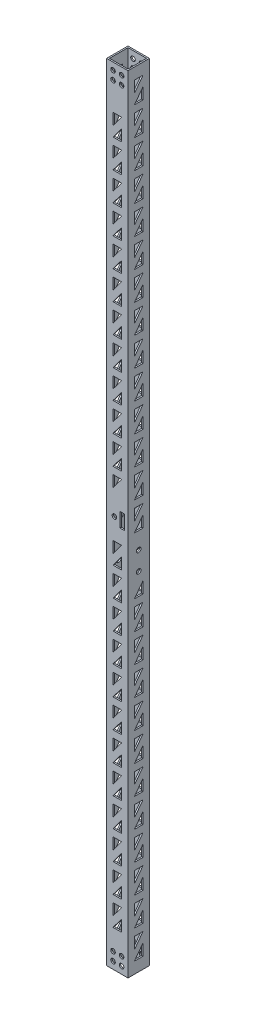
SolidWorks part; units mm, degrees
ref_plane "前视基准面" through (0, 0, 0) normal (0, 0, 1) x (1, 0, 0)
ref_plane "上视基准面" through (0, 0, 0) normal (0, 1, 0) x (1, 0, 0)
ref_plane "右视基准面" through (0, 0, 0) normal (1, 0, 0) x (0, 0, -1)
other "Configuration Table"
sketch "草图1" plane through (0, 0, 0) normal (0, 1, 0) x (1, 0, 0)
  line L1 (6.5, -6.5) -> (-6.5, -6.5)
  line L2 (6.5, -6.5) -> (6.5, 6.5)
  line L3 (6.5, 6.5) -> (-6.5, 6.5)
  line L4 (-6.5, -6.5) -> (-6.5, 6.5)
  line L5 (6.5, -6.5) -> (-6.5, 6.5) construction
  line L6 (6.5, 6.5) -> (-6.5, -6.5) construction
  line L7 (7.5, -7.5) -> (-7.5, -7.5)
  line L8 (7.5, -7.5) -> (7.5, 7.5)
  line L9 (7.5, 7.5) -> (-7.5, 7.5)
  line L10 (-7.5, -7.5) -> (-7.5, 7.5)
  line L11 (7.5, -7.5) -> (-7.5, 7.5) construction
  line L12 (7.5, 7.5) -> (-7.5, -7.5) construction
  point P0 (0, 0)
  point P6 (0, 0)
  dimension "D1" = 13
  dimension "D2" = 15
extrude "凸台-拉伸1" add sketch "草图1" along normal blind 551
sketch "草图2" plane through (0, 0, 7.5) normal (0, 0, 1) x (1, 0, 0)
  line L0 (-7.5, 543) -> (7.5, 543) construction
  line L1 (-7.5, 551) -> (-7.5, 0) construction
  line L2 (7.5, 551) -> (7.5, 0) construction
  line L3 (-7.5, 275.5) -> (7.5, 275.5) construction
  line L4 (-7.5, 551) -> (7.5, 551) construction
  line L5 (0, 549.2213) -> (0, 545.4151) construction
  line L6 (-7.5, 525.5) -> (7.5, 525.5) construction
  line L7 (-7.5, 25.5) -> (7.5, 25.5) construction
  line L8 (-3, 512.5) -> (-3, 520.5)
  line L9 (-3, 520.5) -> (3, 520.5)
  line L10 (3, 520.5) -> (-3, 512.5)
  line L11 (-3, 505.5) -> (3, 505.5)
  line L12 (3, 505.5) -> (3, 513.5)
  line L13 (3, 513.5) -> (-3, 505.5)
  line L14 (3, 500.5) -> (-3, 492.5)
  line L15 (-3, 492.5) -> (-3, 500.5)
  line L16 (-3, 500.5) -> (3, 500.5)
  line L17 (3, 493.5) -> (-3, 485.5)
  line L18 (-3, 485.5) -> (3, 485.5)
  line L19 (3, 485.5) -> (3, 493.5)
  line L20 (3, 480.5) -> (-3, 472.5)
  line L21 (-3, 472.5) -> (-3, 480.5)
  line L22 (-3, 480.5) -> (3, 480.5)
  line L23 (3, 473.5) -> (-3, 465.5)
  line L24 (-3, 465.5) -> (3, 465.5)
  line L25 (3, 465.5) -> (3, 473.5)
  line L26 (3, 460.5) -> (-3, 452.5)
  line L27 (-3, 452.5) -> (-3, 460.5)
  line L28 (-3, 460.5) -> (3, 460.5)
  line L29 (3, 453.5) -> (-3, 445.5)
  line L30 (-3, 445.5) -> (3, 445.5)
  line L31 (3, 445.5) -> (3, 453.5)
  line L32 (3, 440.5) -> (-3, 432.5)
  line L33 (-3, 432.5) -> (-3, 440.5)
  line L34 (-3, 440.5) -> (3, 440.5)
  line L35 (3, 433.5) -> (-3, 425.5)
  line L36 (-3, 425.5) -> (3, 425.5)
  line L37 (3, 425.5) -> (3, 433.5)
  line L38 (3, 420.5) -> (-3, 412.5)
  line L39 (-3, 412.5) -> (-3, 420.5)
  line L40 (-3, 420.5) -> (3, 420.5)
  line L41 (3, 413.5) -> (-3, 405.5)
  line L42 (-3, 405.5) -> (3, 405.5)
  line L43 (3, 405.5) -> (3, 413.5)
  line L44 (3, 400.5) -> (-3, 392.5)
  line L45 (-3, 392.5) -> (-3, 400.5)
  line L46 (-3, 400.5) -> (3, 400.5)
  line L47 (3, 393.5) -> (-3, 385.5)
  line L48 (-3, 385.5) -> (3, 385.5)
  line L49 (3, 385.5) -> (3, 393.5)
  line L50 (3, 380.5) -> (-3, 372.5)
  line L51 (-3, 372.5) -> (-3, 380.5)
  line L52 (-3, 380.5) -> (3, 380.5)
  line L53 (3, 373.5) -> (-3, 365.5)
  line L54 (-3, 365.5) -> (3, 365.5)
  line L55 (3, 365.5) -> (3, 373.5)
  line L56 (3, 360.5) -> (-3, 352.5)
  line L57 (-3, 352.5) -> (-3, 360.5)
  line L58 (-3, 360.5) -> (3, 360.5)
  line L59 (3, 353.5) -> (-3, 345.5)
  line L60 (-3, 345.5) -> (3, 345.5)
  line L61 (3, 345.5) -> (3, 353.5)
  line L62 (3, 340.5) -> (-3, 332.5)
  line L63 (-3, 332.5) -> (-3, 340.5)
  line L64 (-3, 340.5) -> (3, 340.5)
  line L65 (3, 333.5) -> (-3, 325.5)
  line L66 (-3, 325.5) -> (3, 325.5)
  line L67 (3, 325.5) -> (3, 333.5)
  line L68 (3, 320.5) -> (-3, 312.5)
  line L69 (-3, 312.5) -> (-3, 320.5)
  line L70 (-3, 320.5) -> (3, 320.5)
  line L71 (3, 313.5) -> (-3, 305.5)
  line L72 (-3, 305.5) -> (3, 305.5)
  line L73 (3, 305.5) -> (3, 313.5)
  line L74 (3, 300.5) -> (-3, 292.5)
  line L75 (-3, 292.5) -> (-3, 300.5)
  line L76 (-3, 300.5) -> (3, 300.5)
  line L95 (3, 233.5) -> (-3, 225.5)
  line L96 (-3, 225.5) -> (3, 225.5)
  line L97 (3, 225.5) -> (3, 233.5)
  line L98 (3, 220.5) -> (-3, 212.5)
  line L99 (-3, 212.5) -> (-3, 220.5)
  line L100 (-3, 220.5) -> (3, 220.5)
  line L101 (3, 213.5) -> (-3, 205.5)
  line L102 (-3, 205.5) -> (3, 205.5)
  line L103 (3, 205.5) -> (3, 213.5)
  line L104 (3, 200.5) -> (-3, 192.5)
  line L105 (-3, 192.5) -> (-3, 200.5)
  line L106 (-3, 200.5) -> (3, 200.5)
  line L107 (3, 193.5) -> (-3, 185.5)
  line L108 (-3, 185.5) -> (3, 185.5)
  line L109 (3, 185.5) -> (3, 193.5)
  line L110 (3, 180.5) -> (-3, 172.5)
  line L111 (-3, 172.5) -> (-3, 180.5)
  line L112 (-3, 180.5) -> (3, 180.5)
  line L113 (3, 173.5) -> (-3, 165.5)
  line L114 (-3, 165.5) -> (3, 165.5)
  line L115 (3, 165.5) -> (3, 173.5)
  line L116 (3, 160.5) -> (-3, 152.5)
  line L117 (-3, 152.5) -> (-3, 160.5)
  line L118 (-3, 160.5) -> (3, 160.5)
  line L119 (3, 153.5) -> (-3, 145.5)
  line L120 (-3, 145.5) -> (3, 145.5)
  line L121 (3, 145.5) -> (3, 153.5)
  line L122 (3, 140.5) -> (-3, 132.5)
  line L123 (-3, 132.5) -> (-3, 140.5)
  line L124 (-3, 140.5) -> (3, 140.5)
  line L125 (3, 133.5) -> (-3, 125.5)
  line L126 (-3, 125.5) -> (3, 125.5)
  line L127 (3, 125.5) -> (3, 133.5)
  line L128 (3, 120.5) -> (-3, 112.5)
  line L129 (-3, 112.5) -> (-3, 120.5)
  line L130 (-3, 120.5) -> (3, 120.5)
  line L131 (3, 113.5) -> (-3, 105.5)
  line L132 (-3, 105.5) -> (3, 105.5)
  line L133 (3, 105.5) -> (3, 113.5)
  line L134 (3, 100.5) -> (-3, 92.5)
  line L135 (-3, 92.5) -> (-3, 100.5)
  line L136 (-3, 100.5) -> (3, 100.5)
  line L137 (3, 93.5) -> (-3, 85.5)
  line L138 (-3, 85.5) -> (3, 85.5)
  line L139 (3, 85.5) -> (3, 93.5)
  line L140 (3, 80.5) -> (-3, 72.5)
  line L141 (-3, 72.5) -> (-3, 80.5)
  line L142 (-3, 80.5) -> (3, 80.5)
  line L143 (3, 73.5) -> (-3, 65.5)
  line L144 (-3, 65.5) -> (3, 65.5)
  line L145 (3, 65.5) -> (3, 73.5)
  line L146 (3, 60.5) -> (-3, 52.5)
  line L147 (-3, 52.5) -> (-3, 60.5)
  line L148 (-3, 60.5) -> (3, 60.5)
  line L149 (3, 53.5) -> (-3, 45.5)
  line L150 (-3, 45.5) -> (3, 45.5)
  line L151 (3, 45.5) -> (3, 53.5)
  line L152 (3, 40.5) -> (-3, 32.5)
  line L153 (-3, 32.5) -> (-3, 40.5)
  line L154 (-3, 40.5) -> (3, 40.5)
  line L155 (3, 33.5) -> (-3, 25.5)
  line L156 (-3, 25.5) -> (3, 25.5)
  line L157 (3, 25.5) -> (3, 33.5)
  line L158 (3, 253.5) -> (-3, 245.5) [skipped]
  line L159 (3, 245.5) -> (3, 253.5) [skipped]
  line L160 (-3, 245.5) -> (3, 245.5) [skipped]
  line L161 (-3, 252.5) -> (-3, 260.5) [skipped]
  line L162 (-3, 260.5) -> (3, 260.5) [skipped]
  line L163 (3, 260.5) -> (-3, 252.5) [skipped]
  line L164 (-3, 232.5) -> (-3, 240.5) [skipped]
  line L165 (-3, 240.5) -> (3, 240.5) [skipped]
  line L166 (3, 240.5) -> (-3, 232.5) [skipped]
  line L167 (3, 260.5) -> (-3, 252.5)
  line L168 (-3, 252.5) -> (-3, 260.5)
  line L169 (-3, 260.5) -> (3, 260.5)
  line L170 (3, 240.5) -> (-3, 232.5)
  line L171 (-3, 232.5) -> (-3, 240.5)
  line L172 (-3, 240.5) -> (3, 240.5)
  line L173 (3, 253.5) -> (-3, 245.5)
  line L174 (-3, 245.5) -> (3, 245.5)
  line L175 (3, 245.5) -> (3, 253.5)
  line L176 (3, 280.5) -> (-3, 272.5) [skipped]
  line L177 (-3, 272.5) -> (-3, 280.5) [skipped]
  line L178 (-3, 280.5) -> (3, 280.5) [skipped]
  line L179 (3, 293.5) -> (-3, 285.5) [skipped]
  line L180 (-3, 285.5) -> (3, 285.5) [skipped]
  line L181 (3, 285.5) -> (3, 293.5) [skipped]
  line L182 (3, 273.5) -> (-3, 265.5) [skipped]
  line L183 (-3, 265.5) -> (3, 265.5) [skipped]
  line L184 (3, 265.5) -> (3, 273.5) [skipped]
  line L186 (1.95, 270.45) -> (5.05, 270.45)
  line L187 (1.95, 270.45) -> (1.95, 280.55)
  line L188 (1.95, 280.55) -> (5.05, 280.55)
  line L189 (5.05, 270.45) -> (5.05, 280.55)
  line L190 (1.95, 270.45) -> (5.05, 280.55) construction
  line L191 (1.95, 280.55) -> (5.05, 270.45) construction
  circle A0 centre (-3, 546) radius 1.6
  circle A1 centre (3, 546) radius 1.6
  circle A2 centre (-3, 540) radius 1.6
  circle A3 centre (3, 540) radius 1.6
  circle A4 centre (3, 11) radius 1.6
  circle A5 centre (-3, 11) radius 1.6
  circle A6 centre (3, 5) radius 1.6
  circle A7 centre (-3, 5) radius 1.6
  circle A8 centre (-2, 275.5) radius 1.6
  point P109 (0, 275.5)
  point P110 (3.5, 275.5)
  point P115 (0, 0)
  point P116 (0, 0)
  dimension "D2" = 3.2
  dimension "D6" = 3.2
  dimension "D1" = 8
  dimension "D3" = 6
  dimension "D4" = 6
  dimension "D5" = 25.5
  dimension "D7" = 2
  dimension "D8" = 3.1
  dimension "D9" = 6
  dimension "D10" = 8
  dimension "D11" = 5
  dimension "D12" = 8
  dimension "D13" = 6
  dimension "D14" = 15
  dimension "D16" = 1.95
  dimension "D17" = 10.1
  dimension "D15" = 25
extrude "切除-拉伸1" cut sketch "草图2" against normal up to surface (15 mm away) up to face at (0, 275.5, -7.5)
sketch "草图4" plane through (7.5, 0, 0) normal (1, 0, 0) x (0, 0, -1)
  line L0 (0, 279.6032) -> (0, 248.1841) construction
  line L1 (-7.5, 551) -> (7.5, 551) construction
  line L2 (-3, 543) -> (3, 543)
  line L3 (3, 543) -> (-3, 535)
  line L4 (-3, 535) -> (-3, 543)
  line L5 (-3, 528) -> (3, 536)
  line L6 (3, 536) -> (3, 528)
  line L7 (3, 528) -> (-3, 528)
  line L8 (-3, 515) -> (-3, 523)
  line L9 (-3, 523) -> (3, 523)
  line L10 (3, 523) -> (-3, 515)
  line L11 (3, 508) -> (-3, 508)
  line L12 (-3, 508) -> (3, 516)
  line L13 (3, 516) -> (3, 508)
  line L14 (-3, 495) -> (-3, 503)
  line L15 (-3, 503) -> (3, 503)
  line L16 (3, 503) -> (-3, 495)
  line L17 (3, 488) -> (-3, 488)
  line L18 (-3, 488) -> (3, 496)
  line L19 (3, 496) -> (3, 488)
  line L20 (-3, 475) -> (-3, 483)
  line L21 (-3, 483) -> (3, 483)
  line L22 (3, 483) -> (-3, 475)
  line L23 (3, 468) -> (-3, 468)
  line L24 (-3, 468) -> (3, 476)
  line L25 (3, 476) -> (3, 468)
  line L26 (-3, 455) -> (-3, 463)
  line L27 (-3, 463) -> (3, 463)
  line L28 (3, 463) -> (-3, 455)
  line L29 (3, 448) -> (-3, 448)
  line L30 (-3, 448) -> (3, 456)
  line L31 (3, 456) -> (3, 448)
  line L32 (-3, 435) -> (-3, 443)
  line L33 (-3, 443) -> (3, 443)
  line L34 (3, 443) -> (-3, 435)
  line L35 (3, 428) -> (-3, 428)
  line L36 (-3, 428) -> (3, 436)
  line L37 (3, 436) -> (3, 428)
  line L38 (-3, 415) -> (-3, 423)
  line L39 (-3, 423) -> (3, 423)
  line L40 (3, 423) -> (-3, 415)
  line L41 (3, 408) -> (-3, 408)
  line L42 (-3, 408) -> (3, 416)
  line L43 (3, 416) -> (3, 408)
  line L44 (-3, 395) -> (-3, 403)
  line L45 (-3, 403) -> (3, 403)
  line L46 (3, 403) -> (-3, 395)
  line L47 (3, 388) -> (-3, 388)
  line L48 (-3, 388) -> (3, 396)
  line L49 (3, 396) -> (3, 388)
  line L50 (-3, 375) -> (-3, 383)
  line L51 (-3, 383) -> (3, 383)
  line L52 (3, 383) -> (-3, 375)
  line L53 (3, 368) -> (-3, 368)
  line L54 (-3, 368) -> (3, 376)
  line L55 (3, 376) -> (3, 368)
  line L56 (-3, 355) -> (-3, 363)
  line L57 (-3, 363) -> (3, 363)
  line L58 (3, 363) -> (-3, 355)
  line L59 (3, 348) -> (-3, 348)
  line L60 (-3, 348) -> (3, 356)
  line L61 (3, 356) -> (3, 348)
  line L62 (-3, 335) -> (-3, 343)
  line L63 (-3, 343) -> (3, 343)
  line L64 (3, 343) -> (-3, 335)
  line L65 (3, 328) -> (-3, 328)
  line L66 (-3, 328) -> (3, 336)
  line L67 (3, 336) -> (3, 328)
  line L68 (-3, 315) -> (-3, 323)
  line L69 (-3, 323) -> (3, 323)
  line L70 (3, 323) -> (-3, 315)
  line L71 (3, 308) -> (-3, 308)
  line L72 (-3, 308) -> (3, 316)
  line L73 (3, 316) -> (3, 308)
  line L74 (-3, 295) -> (-3, 303)
  line L75 (-3, 303) -> (3, 303)
  line L76 (3, 303) -> (-3, 295)
  line L77 (3, 288) -> (-3, 288)
  line L78 (-3, 288) -> (3, 296)
  line L79 (3, 296) -> (3, 288)
  line L80 (-3, 275) -> (-3, 283)
  line L81 (-3, 283) -> (3, 283)
  line L82 (3, 283) -> (-3, 275)
  line L83 (3, 268) -> (-3, 268)
  line L84 (-3, 268) -> (3, 276)
  line L85 (3, 276) -> (3, 268)
  line L95 (3, 228) -> (-3, 228)
  line L96 (-3, 228) -> (3, 236)
  line L97 (3, 236) -> (3, 228)
  line L98 (-3, 215) -> (-3, 223)
  line L99 (-3, 223) -> (3, 223)
  line L100 (3, 223) -> (-3, 215)
  line L101 (3, 208) -> (-3, 208)
  line L102 (-3, 208) -> (3, 216)
  line L103 (3, 216) -> (3, 208)
  line L104 (-3, 195) -> (-3, 203)
  line L105 (-3, 203) -> (3, 203)
  line L106 (3, 203) -> (-3, 195)
  line L107 (3, 188) -> (-3, 188)
  line L108 (-3, 188) -> (3, 196)
  line L109 (3, 196) -> (3, 188)
  line L110 (-3, 175) -> (-3, 183)
  line L111 (-3, 183) -> (3, 183)
  line L112 (3, 183) -> (-3, 175)
  line L113 (3, 168) -> (-3, 168)
  line L114 (-3, 168) -> (3, 176)
  line L115 (3, 176) -> (3, 168)
  line L116 (-3, 155) -> (-3, 163)
  line L117 (-3, 163) -> (3, 163)
  line L118 (3, 163) -> (-3, 155)
  line L119 (3, 148) -> (-3, 148)
  line L120 (-3, 148) -> (3, 156)
  line L121 (3, 156) -> (3, 148)
  line L122 (-3, 135) -> (-3, 143)
  line L123 (-3, 143) -> (3, 143)
  line L124 (3, 143) -> (-3, 135)
  line L125 (3, 128) -> (-3, 128)
  line L126 (-3, 128) -> (3, 136)
  line L127 (3, 136) -> (3, 128)
  line L128 (-3, 115) -> (-3, 123)
  line L129 (-3, 123) -> (3, 123)
  line L130 (3, 123) -> (-3, 115)
  line L131 (3, 108) -> (-3, 108)
  line L132 (-3, 108) -> (3, 116)
  line L133 (3, 116) -> (3, 108)
  line L134 (-3, 95) -> (-3, 103)
  line L135 (-3, 103) -> (3, 103)
  line L136 (3, 103) -> (-3, 95)
  line L137 (3, 88) -> (-3, 88)
  line L138 (-3, 88) -> (3, 96)
  line L139 (3, 96) -> (3, 88)
  line L140 (-3, 75) -> (-3, 83)
  line L141 (-3, 83) -> (3, 83)
  line L142 (3, 83) -> (-3, 75)
  line L143 (3, 68) -> (-3, 68)
  line L144 (-3, 68) -> (3, 76)
  line L145 (3, 76) -> (3, 68)
  line L146 (-3, 55) -> (-3, 63)
  line L147 (-3, 63) -> (3, 63)
  line L148 (3, 63) -> (-3, 55)
  line L149 (3, 48) -> (-3, 48)
  line L150 (-3, 48) -> (3, 56)
  line L151 (3, 56) -> (3, 48)
  line L152 (-3, 35) -> (-3, 43)
  line L153 (-3, 43) -> (3, 43)
  line L154 (3, 43) -> (-3, 35)
  line L155 (3, 28) -> (-3, 28)
  line L156 (-3, 28) -> (3, 36)
  line L157 (3, 36) -> (3, 28)
  line L158 (-3, 15) -> (-3, 23)
  line L159 (-3, 23) -> (3, 23)
  line L160 (3, 23) -> (-3, 15)
  line L161 (3, 8) -> (-3, 8)
  line L162 (-3, 8) -> (3, 16)
  line L163 (3, 16) -> (3, 8)
  line L166 (-3, 255) -> (-3, 263) [skipped]
  line L167 (-3, 263) -> (3, 263) [skipped]
  line L168 (3, 263) -> (-3, 255) [skipped]
  line L169 (-3, 248) -> (3, 256) [skipped]
  line L170 (3, 256) -> (3, 248) [skipped]
  line L171 (3, 248) -> (-3, 248) [skipped]
  line L172 (-3, 243) -> (3, 243) [skipped]
  line L173 (3, 243) -> (-3, 235) [skipped]
  line L174 (-3, 235) -> (-3, 243) [skipped]
  circle A0 centre (0, 256.2) radius 1.6
  circle A1 centre (0, 243.2) radius 1.6
  point P14 (0, 528)
  dimension "D1" = 3.2
  dimension "D2" = 294.8
  dimension "D3" = 13
  dimension "D4" = 3
  dimension "D5" = 3
  dimension "D6" = 8
  dimension "D7" = 8
  dimension "D8" = 6
  dimension "D9" = 8
  dimension "D10" = 15
  dimension "D11" = 3
  dimension "D12" = 27
extrude "切除-拉伸2" cut sketch "草图4" against normal up to surface (15 mm away) up to face at (-7.5, 275.5, 0)
